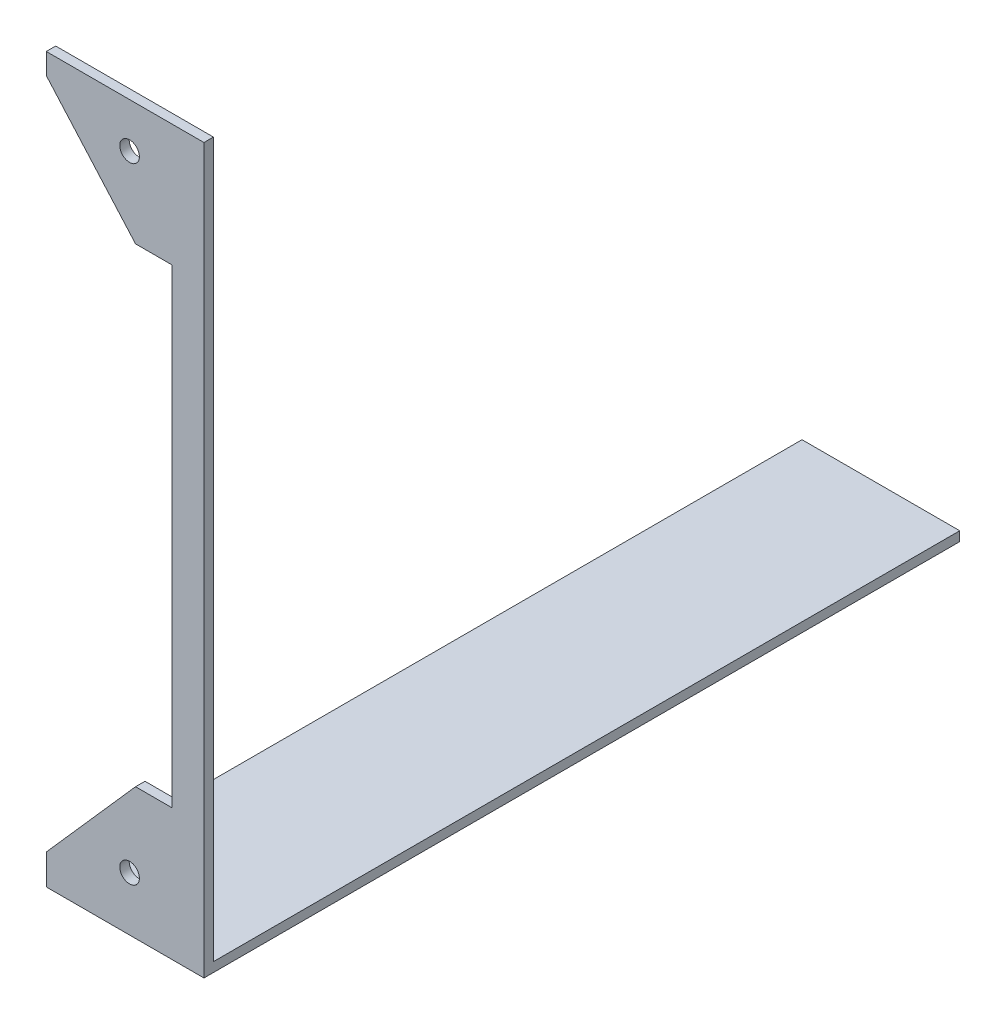
SolidWorks part; units mm, degrees
ref_plane "Front Plane" through (0, 0, 0) normal (0, 0, 1) x (1, 0, 0)
ref_plane "Top Plane" through (0, 0, 0) normal (0, 1, 0) x (1, 0, 0)
ref_plane "Right Plane" through (0, 0, 0) normal (1, 0, 0) x (0, 0, -1)
sketch "Sketch1" plane through (0, 0, 0) normal (0, 0, 1) x (1, 0, 0)
  line L0 (-250, 120) -> (0, 120) construction
  line L1 (0, 118) -> (0, 2) construction
  line L2 (0, 0) -> (-250, 0) construction
  line L3 (-26.5, 116.5) -> (-11.5, 99.5) construction
  line L4 (-11.5, 99.5) -> (-5.4, 99.5) construction
  line L5 (-5.4, 99.5) -> (-5.4, 20.5) construction
  line L6 (-11.5, 20.5) -> (-26.5, 3.5) construction
  line L7 (-5.4, 20.5) -> (-11.5, 20.5) construction
  line L8 (-26.5, 120) -> (0, 120)
  line L9 (0, 120) -> (0, 0)
  line L10 (0, 0) -> (-26.5, 0)
  line L11 (-26.5, 116.5) -> (-11.5, 99.5)
  line L12 (-11.5, 99.5) -> (-5.4, 99.5)
  line L13 (-5.4, 99.5) -> (-5.4, 20.5)
  line L14 (-11.5, 20.5) -> (-26.5, 3.5)
  line L15 (-5.4, 20.5) -> (-11.5, 20.5)
  line L16 (-26.5, 3.5) -> (-26.5, 0)
  line L17 (-26.5, 116.5) -> (-26.5, 120)
  arc A0 (-14.15, 112.5) -> (-10.85, 112.5) centre (-12.5, 112.5) ccw construction
  arc A1 (-10.85, 112.5) -> (-14.15, 112.5) centre (-12.5, 112.5) ccw construction
  arc A2 (-14.15, 7.5) -> (-10.85, 7.5) centre (-12.5, 7.5) ccw construction
  arc A3 (-10.85, 7.5) -> (-14.15, 7.5) centre (-12.5, 7.5) ccw construction
  arc A4 (-14.15, 112.5) -> (-10.85, 112.5) centre (-12.5, 112.5) ccw
  arc A5 (-10.85, 112.5) -> (-14.15, 112.5) centre (-12.5, 112.5) ccw
  arc A6 (-14.15, 7.5) -> (-10.85, 7.5) centre (-12.5, 7.5) ccw
  arc A7 (-10.85, 7.5) -> (-14.15, 7.5) centre (-12.5, 7.5) ccw
extrude "Boss-Extrude1" add sketch "Sketch1" along normal blind 1.5875
sketch "Sketch2" plane through (0, 0, 0) normal (0, 1, 0) x (1, 0, 0)
  line L0 (0, -1.5875) -> (0, 125.4125)
  line L1 (0, 125.4125) -> (-26.5, 125.4125)
  line L2 (-26.5, 125.4125) -> (-26.5, -1.5875)
  line L3 (0, -1.5875) -> (-26.5, -1.5875)
  dimension "D1" = 127
extrude "Boss-Extrude2" add sketch "Sketch2" against normal blind 1.5875
